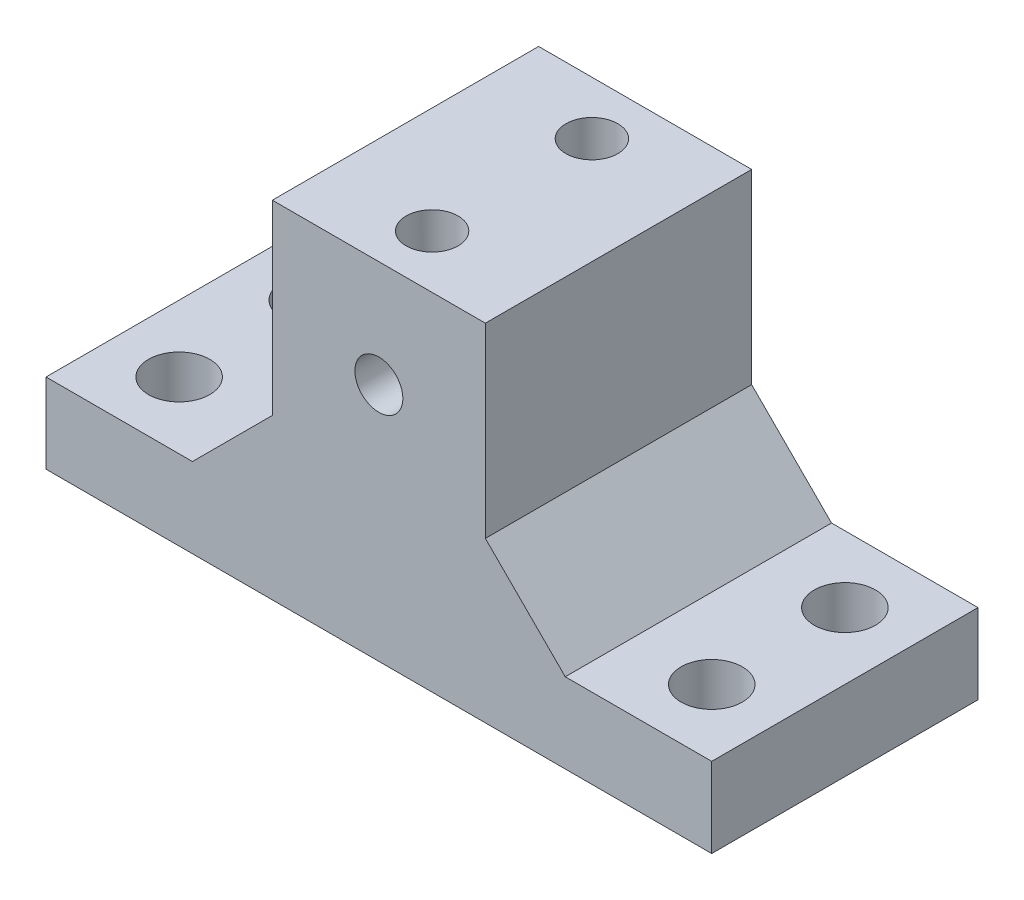
SolidWorks part; units mm, degrees
ref_plane "Front Plane" through (0, 0, 0) normal (0, 0, 1) x (1, 0, 0)
ref_plane "Top Plane" through (0, 0, 0) normal (0, 1, 0) x (1, 0, 0)
ref_plane "Right Plane" through (0, 0, 0) normal (1, 0, 0) x (0, 0, -1)
sketch "Sketch1" plane through (0, 0, 0) normal (0, 1, 0) x (1, 0, 0)
  line L1 (-12.5, -5) -> (12.5, -5)
  line L2 (-12.5, -5) -> (-12.5, 5)
  line L3 (-12.5, 5) -> (12.5, 5)
  line L4 (12.5, -5) -> (12.5, 5)
  line L5 (-12.5, -5) -> (12.5, 5) construction
  line L6 (-12.5, 5) -> (12.5, -5) construction
  line L7 (-10, -2.5) -> (10, -2.5) construction
  line L8 (-10, -2.5) -> (-10, 2.5) construction
  line L9 (-10, 2.5) -> (10, 2.5) construction
  line L10 (10, -2.5) -> (10, 2.5) construction
  line L11 (-10, -2.5) -> (10, 2.5) construction
  line L12 (-10, 2.5) -> (10, -2.5) construction
  circle A0 centre (-10, 2.5) radius 1.15
  circle A1 centre (-10, -2.5) radius 1.15
  circle A2 centre (10, 2.5) radius 1.15
  circle A3 centre (10, -2.5) radius 1.15
  point P0 (0, 0)
  point P6 (0, 0)
  dimension "D3" = 5
  dimension "D5" = 2.3
  dimension "D1" = 25
  dimension "D2" = 10
  dimension "D4" = 20
extrude "Boss-Extrude1" add sketch "Sketch1" along normal blind 3
sketch "Sketch3" plane through (0, 0, -5) normal (0, 0, -1) x (-1, 0, 0)
  line L0 (-12.5, 0) -> (12.5, 0) construction
  line L1 (-4, 0) -> (4, 0)
  line L2 (-4, 0) -> (-4, 13)
  line L3 (-4, 13) -> (4, 13)
  line L4 (4, 0) -> (4, 13)
  line L5 (0, 13) -> (0, 0) construction
  dimension "D1" = 13
  dimension "D2" = 8
extrude "Boss-Extrude2" add sketch "Sketch3" against normal up to surface (10 mm away) up to face at (0, 1.5, 5)
sketch "Sketch4" plane through (0, 0, -5) normal (0, 0, -1) x (-1, 0, 0)
  line L0 (0, 0) -> (0, 9) construction
  circle A0 centre (0, 9) radius 0.9
  dimension "D2" = 1.8
  dimension "D1" = 9
extrude "Cut-Extrude1" cut sketch "Sketch4" against normal through all
sketch "Sketch5" plane through (0, 13, 0) normal (0, 1, 0) x (1, 0, 0)
  line L0 (0, 3) -> (0, -3) construction
  line L1 (-4, 5) -> (4, 5) construction
  circle A0 centre (0, 3) radius 0.975
  circle A2 centre (0, -3) radius 0.975
  dimension "D1" = 1.95
  dimension "D2" = 2
extrude "Cut-Extrude2" cut sketch "Sketch5" against normal blind 3.5
chamfer "Chamfer1" distance 3 angle 45 2 edges at (-4, 3, 0) (4, 3, 0)
